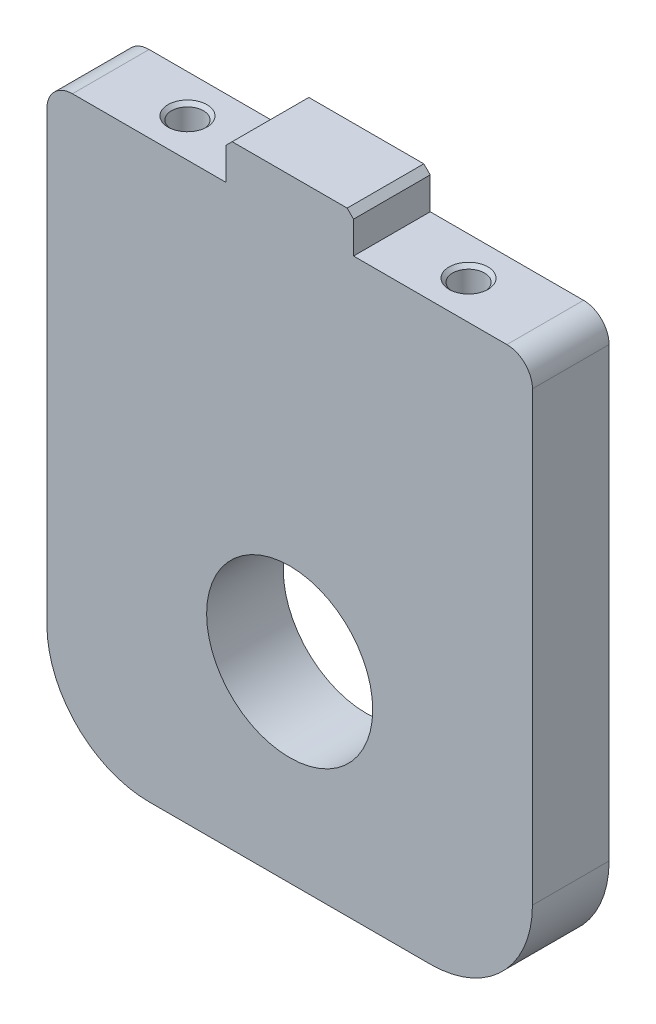
SolidWorks part; units mm, degrees
material "6061 合金"
ref_plane "前视基准面" through (0, 0, 0) normal (0, 0, 1) x (1, 0, 0)
ref_plane "上视基准面" through (0, 0, 0) normal (0, 1, 0) x (1, 0, 0)
ref_plane "右视基准面" through (0, 0, 0) normal (1, 0, 0) x (0, 0, -1)
sketch "草图1" plane through (0, 0, 0) normal (0, 0, 1) x (1, 0, 0)
  line L1 (-19, 22.5) -> (19, 22.5)
  line L2 (-19, 22.5) -> (-19, -22.5)
  line L3 (-19, -22.5) -> (19, -22.5)
  line L4 (19, 22.5) -> (19, -22.5)
  line L5 (-19, 22.5) -> (19, -22.5) construction
  line L6 (-19, -22.5) -> (19, 22.5) construction
  point P0 (0, 0)
  dimension "D1" = 45
  dimension "D2" = 38
extrude "凸台-拉伸1" add sketch "草图1" along normal blind 6
sketch "草图2" plane through (0, 0, 6) normal (0, 0, 1) x (1, 0, 0)
  line L0 (0, 0) -> (0, -18.0777) construction
  line L1 (-19, -22.5) -> (19, -22.5) construction
  circle A0 centre (0, -7.5) radius 6.5
  dimension "D1" = 13
  dimension "D2" = 15
extrude "切除-拉伸1" cut sketch "草图2" against normal through all
fillet "圆角1" radius 2 2 edges at (-19, 22.5, 3) (19, 22.5, 3)
fillet "圆角2" radius 8 2 edges at (-19, -22.5, 3) (19, -22.5, 3)
sketch "草图3" plane through (0, 0, 6) normal (0, 0, 1) x (1, 0, 0)
  line L0 (0, 30.1083) -> (0, 7.6765) construction
  line L1 (-5, 22.5) -> (-5, 25.5)
  line L2 (17, 22.5) -> (-17, 22.5) construction
  line L3 (5, 22.5) -> (5, 25.5)
  line L4 (-5, 25.5) -> (5, 25.5)
  line L5 (5, 22.5) -> (-5, 22.5)
  dimension "D1" = 10
  dimension "D2" = 3
extrude "凸台-拉伸2" add sketch "草图3" against normal up to surface (6 mm away) up to face at (6.5, -7.5, 0)
chamfer "倒角1" distance 0.5 angle 45 2 edges at (5, 25.5, 3) (-5, 25.5, 3)
sketch "草图4" plane through (0, 22.5, 0) normal (0, 1, 0) x (1, 0, 0)
  line L0 (-17, -3) -> (17, -3) construction
  line L1 (-17, 0) -> (-17, -6) construction
  line L2 (17, -6) -> (17, 0) construction
  line L3 (0, 6.4931) -> (0, -10.0268) construction
  point P9 (11, -3)
  point P10 (-11, -3)
  dimension "D1" = 22
hole_wizard "M3 螺纹孔1" positions "3D草图1" profile "草图5" tap size "M3" standard "GB"
sketch3d "3D草图1"
  line L0 (-17, 22.5, 3) -> (17, 22.5, 3) construction
  point P0 (-11, 22.5, 3)
  point P2 (11, 22.5, 3)
  point P5 (-8.5731, 22.5, 3)
  point P8 (-11, 22.5, 3)
  point P10 (11, 22.5, 3)
sketch "草图5" plane through (-11, 22.5, 3) normal (1, 0, 0) x (0, 0, 1)
  line L0 (0, 0) -> (0, 8.2511)
  line L1 (0, 8.2511) -> (1.25, 7.5)
  line L2 (1.25, 7.5) -> (1.25, 0.275)
  line L3 (1.25, 0.275) -> (1.525, 0)
  line L5 (1.525, 0) -> (0, 0)
  line L6 (-1.25, 0.275) -> (-1.525, 0) construction
  line L10 (0, 8.2511) -> (-1.25, 7.5) construction
  line L11 (0, -6.35) -> (0, 107.95) construction
  dimension "螺纹孔钻头直径" = 2.5
  dimension "螺纹孔钻头深度" = 7.5
  dimension "近端锥形沉头孔直径" = 3.05
  dimension "近端锥形沉头孔角度" = 90
  dimension "导头角度" = 118
cosmetic thread "孔螺蚊线1"
cosmetic thread "孔螺蚊线2"
